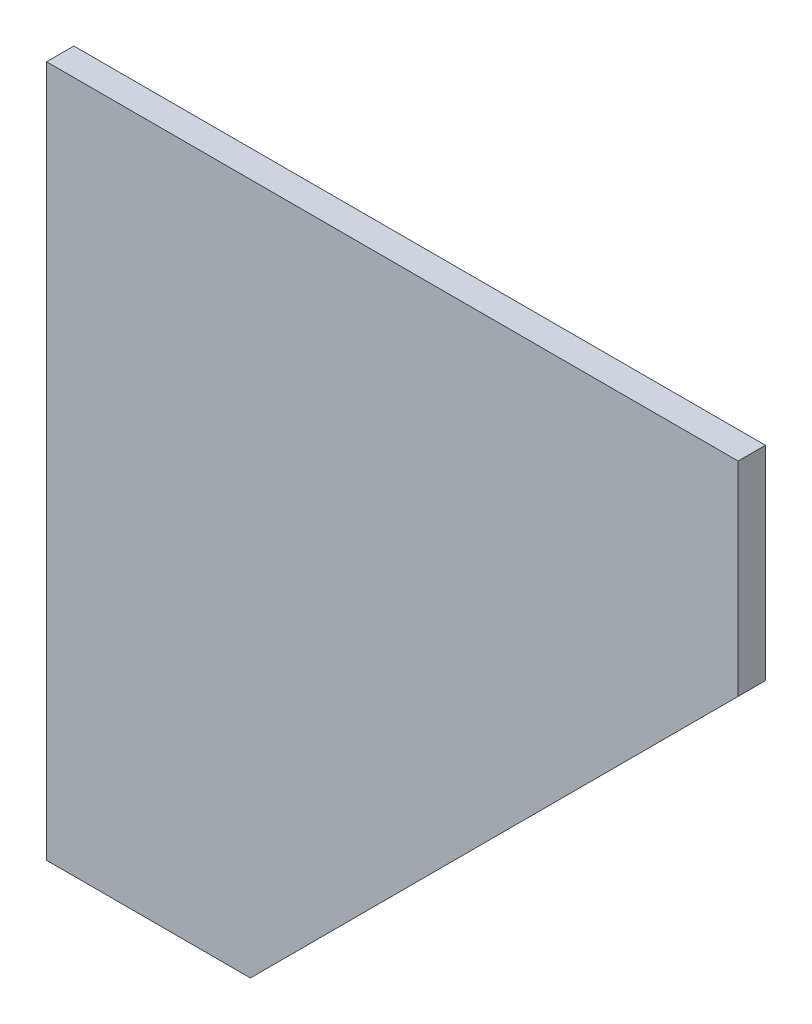
SolidWorks part; units mm, degrees
material "Pine"
ref_plane "Front Plane" through (0, 0, 0) normal (0, 0, 1) x (1, 0, 0)
ref_plane "Top Plane" through (0, 0, 0) normal (0, 1, 0) x (1, 0, 0)
ref_plane "Right Plane" through (0, 0, 0) normal (1, 0, 0) x (0, 0, -1)
sketch "Sketch1" plane through (0, 0, 0) normal (0, 0, 1) x (1, 0, 0)
  line L1 (-150.8125, -150.8125) -> (150.8125, -150.8125)
  line L2 (-150.8125, -150.8125) -> (-150.8125, 150.8125)
  line L3 (-150.8125, 150.8125) -> (150.8125, 150.8125)
  line L4 (150.8125, -150.8125) -> (150.8125, 150.8125)
  line L5 (-150.8125, -150.8125) -> (150.8125, 150.8125) construction
  line L6 (-150.8125, 150.8125) -> (150.8125, -150.8125) construction
  point P0 (0, 0)
  dimension "D1" = 301.625
extrude "Boss-Extrude1" add sketch "Sketch1" along normal blind 11.9062
chamfer "Chamfer1" distance 212.725 1 edges at (150.8125, -150.8125, 5.9531)
